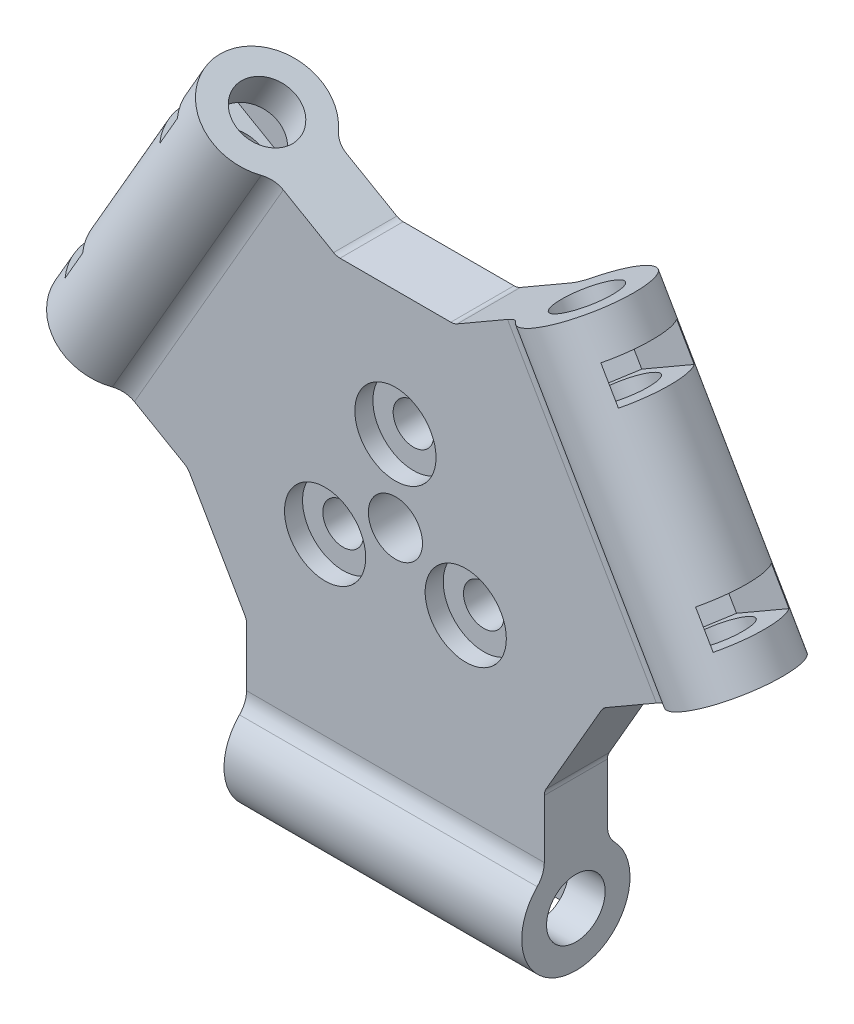
SolidWorks part; units mm, degrees
ref_plane "정면" through (0, 0, 0) normal (0, 0, 1) x (1, 0, 0)
ref_plane "윗면" through (0, 0, 0) normal (0, 1, 0) x (1, 0, 0)
ref_plane "우측면" through (0, 0, 0) normal (1, 0, 0) x (0, 0, -1)
sketch "스케치1" plane through (0, 0, 0) normal (0, 0, 1) x (1, 0, 0)
  line L1 (0, -30) -> (25.9808, 15)
  line L2 (25.9808, 15) -> (-25.9808, 15)
  line L3 (-25.9808, 15) -> (0, -30)
  circle A0 centre (0, 0) radius 15 construction
  dimension "D1" = 30
sketch "스케치2" plane through (0, 0, 0) normal (1, 0, 0) x (0, 0, -1)
  circle A0 centre (0, -30) radius 6
  dimension "D1" = 12
extrude "보스-돌출1" add sketch "스케치2" along normal mid plane 33
sketch "스케치3" plane through (16.5, 0, 0) normal (1, 0, 0) x (0, 0, -1)
  line L0 (0, 15) -> (0, -30) construction
  circle A0 centre (0, -30) radius 3.25
  circle A1 centre (0, -30) radius 6 construction
  dimension "D1" = 6.5
extrude "컷-돌출1" cut sketch "스케치3" against normal blind 13
sketch "스케치4" plane through (-16.5, 0, 0) normal (-1, 0, 0) x (0, 0, 1)
  circle A0 centre (0, -30) radius 3.25
  dimension "D1" = 6.5
extrude "컷-돌출2" cut sketch "스케치4" against normal blind 13
sketch "스케치6" plane through (0, 0, 0) normal (1, 0, 0) x (0, 0, -1)
  line L0 (0, 0) -> (0, -64.4402) construction
  line L2 (-3.5, -23.8763) -> (-3.5, -22)
  line L3 (-3.5, -22) -> (3.5, -22)
  line L4 (3.5, -23.8763) -> (3.5, -22)
  line L5 (4.2857, -25.8009) -> (-4.2857, -25.8009)
  arc A0 (-3.5, -23.8763) -> (-4.2857, -25.8009) centre (-6.25, -23.8763) cw
  circle A2 centre (0, -30) radius 3.25 construction
  circle A3 centre (0, -30) radius 6 construction
  arc A6 (3.5, -23.8763) -> (4.2857, -25.8009) centre (6.25, -23.8763) ccw
  dimension "D4" = 8
  dimension "D2" = 2.75
  dimension "D1" = 7
extrude "보스-돌출2" add sketch "스케치6" along normal mid plane 33
ref_plane "평면1" through (-10.5, 0, 0) normal (-1, 0, 0) x (0, 0, 1)
sketch "스케치12" plane through (-10.5, 0, 0) normal (-1, 0, 0) x (0, 0, 1)
  line L0 (-4.2, -32.4249) -> (-4.2, -36)
  line L1 (0, -34.8497) -> (4.2, -32.4249)
  line L2 (4.2, -32.4249) -> (4.2, -27.5751)
  line L3 (4.2, -27.5751) -> (0, -25.1503)
  line L4 (0, -25.1503) -> (-4.2, -27.5751)
  line L5 (-4.2, -27.5751) -> (-4.2, -32.4249)
  line L6 (-4.2, -32.4249) -> (0, -34.8497)
  line L7 (-4.2, -36) -> (4.2, -36)
  line L8 (4.2, -36) -> (4.2, -32.4249)
  circle A0 centre (0, -30) radius 4.2 construction
  arc A1 (-4.2857, -25.8009) -> (4.2857, -25.8009) centre (0, -30) ccw construction
  dimension "D1" = 8.4
extrude "컷-돌출4" cut sketch "스케치12" against normal blind 1.95 and the other way blind 1.95 contours L7 L8 L1 L6 L0 | L5 L6 L1 L2 L3 L4
ref_plane "평면2" through (10.5, 0, 0) normal (1, 0, 0) x (0, 0, -1)
sketch "스케치13" plane through (10.5, 0, 0) normal (1, 0, 0) x (0, 0, -1)
  line L4 (-4.2, -27.5751) -> (-4.2, -34.2849)
  line L5 (0, -25.1503) -> (-4.2, -27.5751)
  line L6 (4.2, -27.5751) -> (0, -25.1503)
  line L7 (4.2, -34.2849) -> (4.2, -27.5751)
  line L8 (-4.2, -27.5751) -> (-4.2, -34.2849)
  line L9 (0, -25.1503) -> (-4.2, -27.5751)
  line L10 (4.2, -27.5751) -> (0, -25.1503)
  line L11 (4.2, -34.2849) -> (4.2, -27.5751)
  arc A1 (-4.2, -34.2849) -> (4.2, -34.2849) centre (0, -30) ccw
  arc A2 (-4.2, -34.2849) -> (4.2, -34.2849) centre (0, -30) ccw
  dimension "D1" = 0
extrude "컷-돌출5" cut sketch "스케치13" against normal blind 1.95 and the other way blind 1.95
sketch "스케치7" plane through (0, 0, 0) normal (1, 0, 0) x (0, 0, -1)
  line L0 (0, 0) -> (11.1249, 0) construction
pattern_circular "원형 패턴1" count 3 over 360 about axis through (0, 0, 0) along (0, 0, 1) of bodies 112 104
sketch "스케치8" plane through (0, 0, 0) normal (0, 0, 1) x (1, 0, 0)
  line L1 (16.5, -22) -> (-16.5, -22)
  line L5 (10.8026, 25.2894) -> (27.3026, -3.2894)
  line L6 (-10.8026, 25.2894) -> (-12.4275, 26.2276) construction
  line L7 (-6.8485, 23.0066) -> (-10.8026, 25.2894)
  line L8 (0, 0) -> (0, 39.0083) construction
  line L9 (6.8485, 23.0066) -> (10.8026, 25.2894)
  line L15 (-6.1406, 22.8169) -> (6.1406, 22.8169)
  line L16 (23.3485, -5.5723) -> (27.3026, -3.2894)
  line L17 (16.5, -17.4343) -> (16.5, -22)
  line L18 (22.8303, -6.0905) -> (16.6897, -16.7263)
  line L19 (0, 0) -> (33.7822, -19.5041) construction
  line L20 (-27.3026, -3.2894) -> (-10.8026, 25.2894)
  line L21 (-16.5, -17.4343) -> (-16.5, -22)
  line L22 (-23.3485, -5.5723) -> (-27.3026, -3.2894)
  line L23 (-16.6897, -16.7263) -> (-22.8303, -6.0905)
  line L24 (0, 0) -> (-33.7822, -19.5041) construction
  arc A3 (-6.8485, 23.0066) -> (-6.1406, 22.8169) centre (-6.1406, 24.2328) ccw
  arc A4 (6.8485, 23.0066) -> (6.1406, 22.8169) centre (6.1406, 24.2328) cw
  arc A9 (23.3485, -5.5723) -> (22.8303, -6.0905) centre (24.0565, -6.7985) ccw
  arc A10 (16.5, -17.4343) -> (16.6897, -16.7263) centre (17.9159, -17.4343) cw
  arc A11 (-16.5, -17.4343) -> (-16.6897, -16.7263) centre (-17.9159, -17.4343) ccw
  arc A12 (-23.3485, -5.5723) -> (-22.8303, -6.0905) centre (-24.0565, -6.7985) cw
  point P38 (0, 0)
  dimension "D1" = 3
extrude "보스-돌출3" add sketch "스케치8" along normal mid plane 7
sketch "스케치9" plane through (0, 0, 0) normal (0, 0, 1) x (1, 0, 0)
  circle A0 centre (0, 0) radius 3
  dimension "D1" = 6
extrude "컷-돌출3" cut sketch "스케치9" against normal through all both and the other way through all
hole_wizard "M4 남비 머리 나사용 카운터보어1" positions "스케치10" profile "스케치11" counterbore size "M4" standard "ISO" end condition through all
sketch "스케치10" plane through (0, 0, 3.5) normal (0, 0, 1) x (1, 0, 0)
  point P0 (0, 9)
  point P10 (7.7942, -4.5)
  point P11 (-7.7942, -4.5)
  dimension "D1" = 9
  dimension "D2" = 3
sketch "스케치11" plane through (0, 9, 3.5) normal (1, 0, 0) x (0, -1, 0)
  line L0 (0, 0) -> (0, 9.5)
  line L1 (0, 9.5) -> (2.25, 9.5)
  line L3 (2.25, 9.5) -> (2.25, 2)
  line L4 (2.25, 2) -> (4.5, 2)
  line L5 (4.5, 2) -> (4.5, 0)
  line L7 (4.5, 0) -> (0, 0)
  line L11 (0, -6.35) -> (0, 107.95) construction
  dimension "관통 구멍 지름" = 4.5
  dimension "관통 구멍 깊이" = 9.5
  dimension "카운터보어 지름" = 9
  dimension "카운터보어 깊이" = 2
